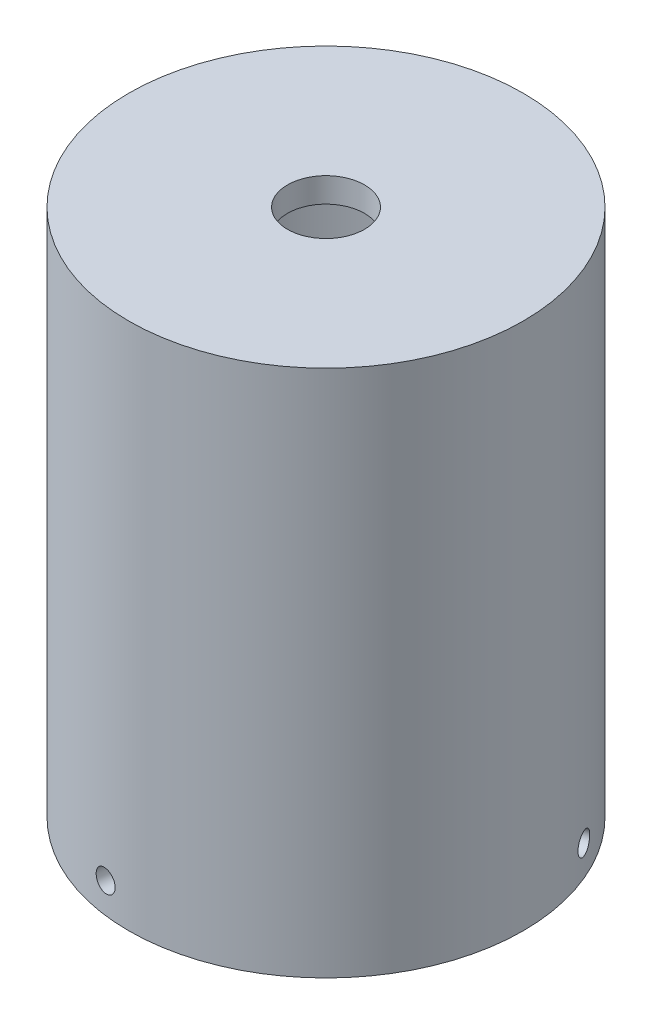
SolidWorks part; units mm, degrees
ref_plane "Front Plane" through (0, 0, 0) normal (0, 0, 1) x (1, 0, 0)
ref_plane "Top Plane" through (0, 0, 0) normal (0, 1, 0) x (1, 0, 0)
ref_plane "Right Plane" through (0, 0, 0) normal (1, 0, 0) x (0, 0, -1)
sketch "Sketch1" plane through (0, 0, 0) normal (0, 1, 0) x (1, 0, 0)
  circle A0 centre (0, 0) radius 20.32
  dimension "D1" = 40.64
extrude "Boss-Extrude1" add sketch "Sketch1" along normal blind 58.7045
shell "Shell1" thickness 2.54
sketch "Sketch2" plane through (0, 56.1645, 0) normal (0, -1, 0) x (1, 0, 0)
  circle A0 centre (0, 0) radius 3.9688
  dimension "D1" = 7.9375
extrude "Cut-Extrude1" cut sketch "Sketch2" against normal through all contours A0
hole_wizard "Tap Drill for #0-80 Tap1" [suppressed] positions "3DSketch2" profile "Sketch4" hole size "#0-80" standard "ANSI Inch"
sketch3d "3DSketch2"
  point P0 (-0.4149, 46.6594, 20.3158)
sketch "Sketch4" plane through (-0.4149, 46.6594, 20.3158) normal (0, 1, 0) x (0.9998, 0, 0.0204)
  line L0 (0, 0) -> (0, 7.6821)
  line L1 (0, 7.6821) -> (1.5875, 6.35)
  line L2 (1.5875, 6.35) -> (1.5875, 0)
  line L5 (1.5875, 0) -> (0, 0)
  line L10 (0, 7.6821) -> (-1.5875, 6.35) construction
  line L11 (0, -6.35) -> (0, 107.95) construction
  dimension "Hole Dia." = 3.175
  dimension "Hole Depth" = 6.35
  dimension "Drill Angle" = 100
ref_plane "Plane1" [suppressed] through (0, 7.4955, 0) normal (0, 1, 0) x (0.9873, 0, 0.1589)
hole_wizard "#2 Clearance Hole1" positions "3DSketch4" profile "Sketch8" hole size "#2" standard "ANSI Inch"
sketch3d "3DSketch4"
  point P0 (-2.5688, 7.425, 20.157)
sketch "Sketch8" plane through (-2.5688, 7.425, 20.157) normal (0, 1, 0) x (0.992, 0, 0.1264)
  line L0 (0, 0) -> (0, 9.8384)
  line L1 (0, 9.8384) -> (1.1303, 8.89)
  line L2 (1.1303, 8.89) -> (1.1303, 0)
  line L5 (1.1303, 0) -> (0, 0)
  line L10 (0, 9.8384) -> (-1.1303, 8.89) construction
  line L11 (0, -6.35) -> (0, 107.95) construction
  dimension "Hole Dia." = 2.2606
  dimension "Hole Depth" = 8.89
  dimension "Drill Angle" = 100
pattern_circular "CirPattern1" count 3 every 120 about axis through (0, 58.7045, 0) along (0, -1, 0) of "#2 Clearance Hole1"
sketch "Sketch9" plane through (0, 0, 0) normal (0, -1, 0) x (1, 0, 0)
  circle A0 centre (0, 0) radius 20.32
extrude "Cut-Extrude2" cut sketch "Sketch9" against normal blind 4.318
